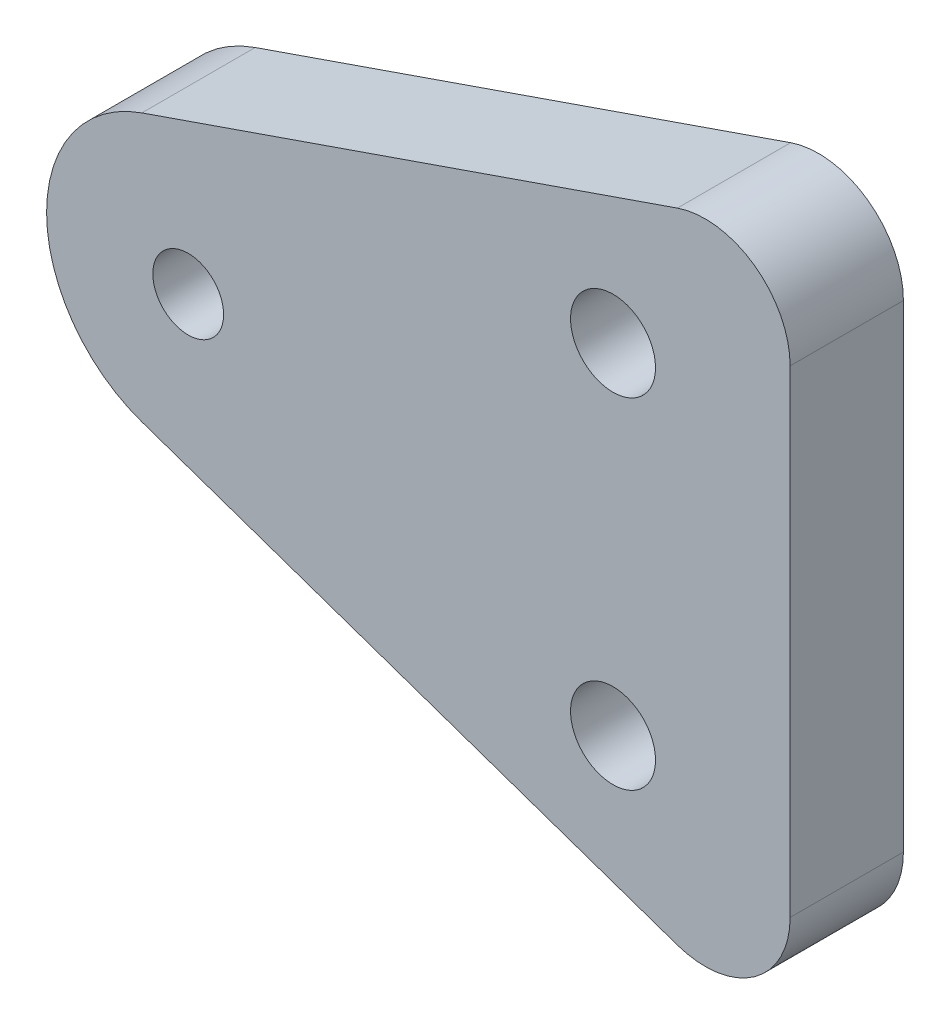
SolidWorks part; units mm, degrees
material "普通碳钢"
ref_plane "前视" through (0, 0, 0) normal (0, 0, 1) x (1, 0, 0)
ref_plane "上视" through (0, 0, 0) normal (0, 1, 0) x (1, 0, 0)
ref_plane "右视" through (0, 0, 0) normal (1, 0, 0) x (0, 0, -1)
sketch "草图1" plane through (0, 0, 0) normal (0, 0, 1) x (1, 0, 0)
  line L0 (-5, 20) -> (16.2529, 20) construction
  line L2 (-6.6351, 15.2749) -> (16.2529, 7.3546)
  line L3 (16.2529, 7.3546) -> (-6.6351, 15.2749) construction
  line L4 (16.2529, 7.3546) -> (16.2529, 32.6454)
  line L5 (-6.6351, 24.7251) -> (16.5085, 32.7338) construction
  line L6 (16.2529, 32.6454) -> (-6.6351, 24.7251)
  arc A0 (-6.6351, 24.7251) -> (-6.6351, 15.2749) centre (-5, 20) ccw
  arc A2 (17.5707, 5.1296) -> (16.2529, 7.3546) centre (15.5989, 5.4646) ccw construction
  circle A3 centre (-5, 20) radius 1.25
  circle A4 centre (10, 26) radius 1.5
  circle A5 centre (10, 14) radius 1.5
  point P2 (0, 0)
  dimension "D1" = 3
  dimension "D3" = 15
  dimension "D4" = 2.5
  dimension "D2" = 12
extrude "凸台-拉伸1" add sketch "草图1" along normal blind 4
fillet "圆角1" radius 3 2 edges at (16.2529, 7.3546, 2) (16.2529, 32.6454, 2)
